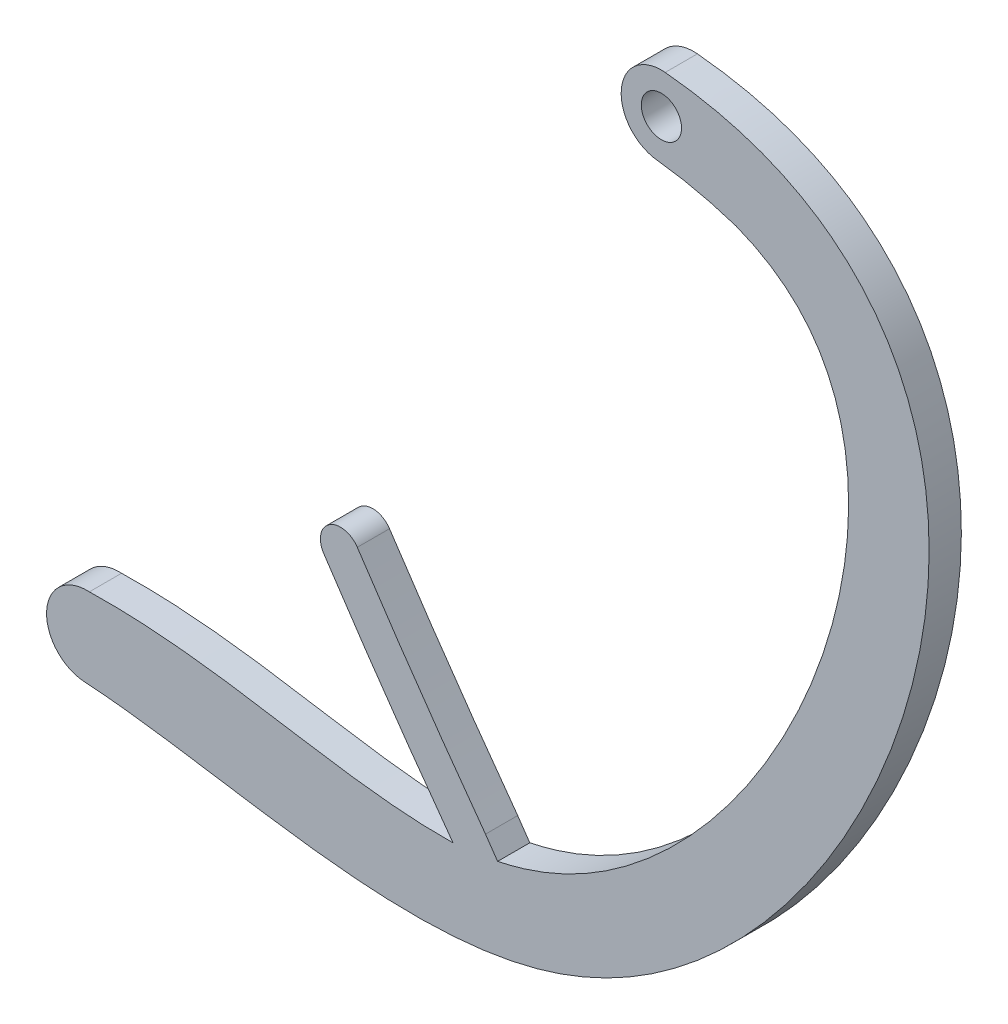
SolidWorks part; units mm, degrees
ref_plane "Front Plane" through (0, 0, 0) normal (0, 0, 1) x (1, 0, 0)
ref_plane "Top Plane" through (0, 0, 0) normal (0, 1, 0) x (1, 0, 0)
ref_plane "Right Plane" through (0, 0, 0) normal (1, 0, 0) x (0, 0, -1)
sketch "Sketch1" plane through (0, 0, 0) normal (0, 0, 1) x (1, 0, 0)
  arc A0 (16.1857, -14.8286) -> (16.1857, -14.8286) centre (16.1857, -14.8286) cw
  arc A1 (-34.8399, -65.3246) -> (-35.2368, -71.6621) centre (-35.0383, -68.4933) ccw
  arc A2 (10.5864, -7.1261) -> (9.9876, -13.4479) centre (10.287, -10.287) ccw
  arc A3 (-13.7012, -51.7119) -> (-16.3527, -53.4584) centre (-15.0269, -52.5852) ccw
  spline S0 degree 1 poles (16.1857, -14.8286) (-34.8399, -65.3246) knots 0 0 1 1 construction
  spline S1 degree 3 poles (16.1857, -14.8286) (16.6266, -14.9998) (17.5163, -15.3894) (19.0486, -16.2337) (20.6659, -17.4471) (22.1922, -19.1303) (23.7874, -21.7208) (25.0194, -25.6972) (25.1871, -31.5672) (23.9979, -38.1113) (20.7453, -47.1329) (15.3297, -55.7036) (8.6218, -62.2815) (4.2057, -65.207) (0.5731, -66.7884) (-3.0322, -67.846) (-7.9637, -68.3901) (-14.3347, -68.0859) (-23.2609, -66.8515) (-30.216, -65.6142) (-34.8399, -65.3246) knots 0.054733 0.054733 0.054733 0.054733 0.069503 0.084273 0.113813 0.143352 0.172892 0.231971 0.29105 0.350129 0.409208 0.527367 0.586446 0.645525 0.675065 0.704604 0.763683 0.822763 0.881842 1 1 1 1 only from (16.1857, -14.8286) to (-2.6332, -67.6332)
  spline S2 degree 2 poles (16.1857, -14.8286) (13.1593, -13.8184) (9.9876, -13.4479) knots 0 0 0 1 1 1
  spline S3 degree 3 poles (-6.1492, -68.1283) (-9.6742, -63.324) (-13.0754, -58.4341) (-16.3527, -53.4584) knots 0 0 0 0 1 1 1 1
  spline S4 degree 1 poles (-3.5893, -66.25) (-13.7012, -51.7119) knots 0 0 1 1 construction
  spline S5 degree 3 poles (10.5864, -7.1261) (11.0025, -7.1656) (11.842, -7.2596) (13.4458, -7.4978) (15.3585, -7.8928) (17.4937, -8.5163) (20.1344, -9.5413) (23.0479, -11.1729) (25.9215, -13.639) (28.1703, -16.5399) (30.3566, -20.8773) (31.6512, -26.9782) (31.2409, -34.9088) (29.156, -43.0691) (25.636, -51.0763) (20.9007, -58.5388) (15.151, -65.0507) (8.588, -70.2142) (1.3352, -73.5325) (-6.1973, -74.7302) (-13.767, -74.5436) (-19.9971, -73.7235) (-24.8635, -72.9623) (-28.4364, -72.4081) (-31.3286, -72.0183) (-33.588, -71.7828) (-34.6838, -71.6968) (-35.2368, -71.6621) knots 0 0 0 0 0.007812 0.015625 0.03125 0.046875 0.0625 0.09375 0.125 0.15625 0.1875 0.25 0.3125 0.375 0.4375 0.5 0.5625 0.625 0.6875 0.75 0.8125 0.875 0.90625 0.9375 0.96875 0.984375 1 1 1 1
  spline S6 degree 3 poles (-3.5893, -66.25) (-7.0814, -61.4908) (-10.4542, -56.6416) (-13.7012, -51.7119) knots 0 0 0 0 1 1 1 1
  spline S7 degree 1 poles (-3.5893, -66.25) (-2.6332, -67.6332) knots 0 0 1 1
  spline S8 degree 3 poles (-6.1492, -68.1283) (-11.7544, -68.2162) (-21.1789, -66.2415) (-30.779, -65.2152) (-34.8399, -65.3246) knots 0 0 0 0 0.578093 1 1 1 1
  dimension "D1" = 3.175
  dimension "D2" = 6.35
  dimension "D3" = 3.175
extrude "Boss-Extrude1" add sketch "Sketch1" along normal blind 2.54 contours S1 S7 S6 A3 S3 S8 A1 S5 A2 S2
sketch "Sketch3" plane through (0, 0, 0) normal (0, 0, -1) x (-1, 0, 0)
  circle A0 centre (-10.287, -10.287) radius 1.5875
  dimension "D1" = 3.175
extrude "Cut-Extrude1" cut sketch "Sketch3" against normal up to next contours A0
